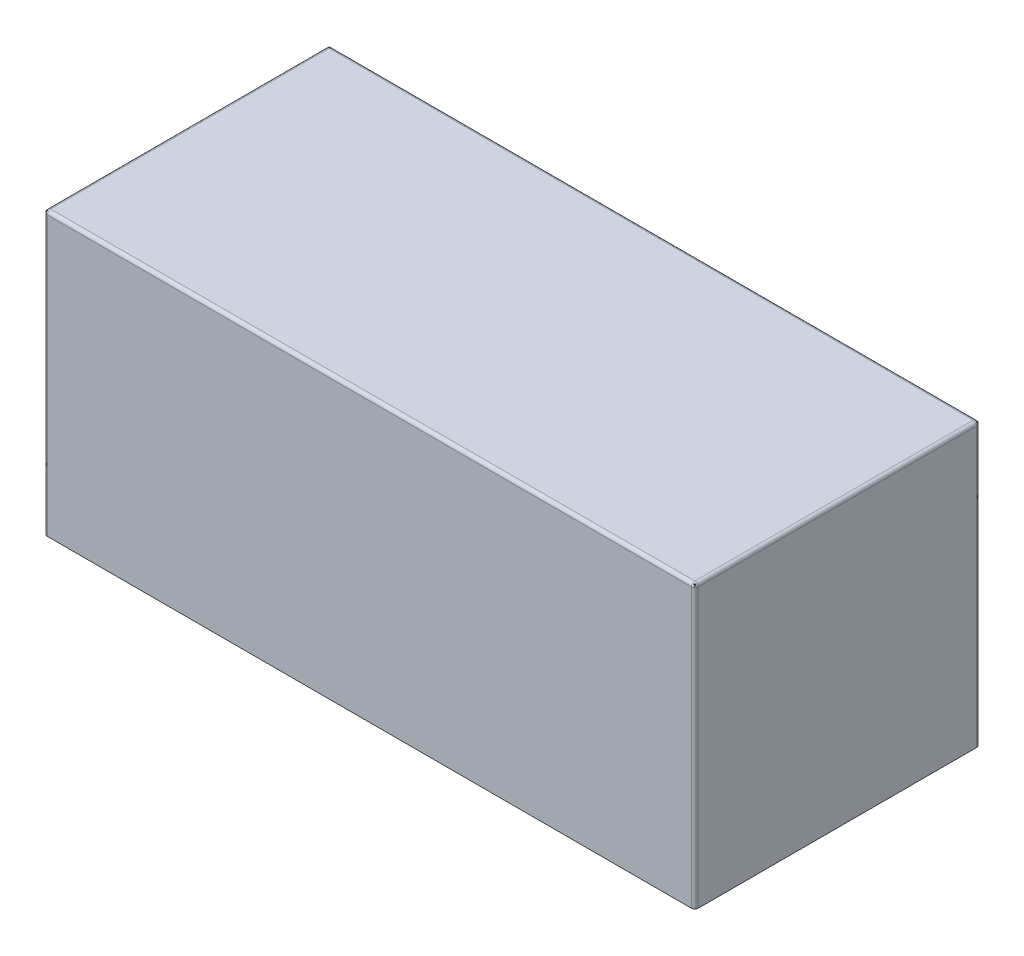
SolidWorks part; units mm, degrees
ref_plane "Front Plane" through (0, 0, 0) normal (0, 0, 1) x (1, 0, 0)
ref_plane "Top Plane" through (0, 0, 0) normal (0, 1, 0) x (1, 0, 0)
ref_plane "Right Plane" through (0, 0, 0) normal (1, 0, 0) x (0, 0, -1)
sketch "Sketch2" plane through (0, 0, 0) normal (0, 1, 0) x (1, 0, 0)
  line L1 (-485, 212.5) -> (485, 212.5)
  line L2 (-485, 212.5) -> (-485, -212.5)
  line L3 (-485, -212.5) -> (485, -212.5)
  line L4 (485, 212.5) -> (485, -212.5)
  line L5 (-485, 212.5) -> (485, -212.5) construction
  line L6 (-485, -212.5) -> (485, 212.5) construction
  line L7 (-483.4125, 210.9125) -> (483.4125, 210.9125)
  line L8 (-483.4125, 210.9125) -> (-483.4125, -210.9125)
  line L9 (-483.4125, -210.9125) -> (483.4125, -210.9125)
  line L10 (483.4125, 210.9125) -> (483.4125, -210.9125)
  line L11 (-483.4125, 210.9125) -> (483.4125, -210.9125) construction
  line L12 (-483.4125, -210.9125) -> (483.4125, 210.9125) construction
  point P0 (0, 0)
  point P6 (0, 0)
  dimension "D1" = 970
  dimension "D2" = 425
  dimension "D3" = 966.825
  dimension "D4" = 421.825
extrude "Boss-Extrude1" add sketch "Sketch2" along normal blind 420
sketch "Sketch3" plane through (0, 0, 0) normal (0, 1, 0) x (1, 0, 0)
  line L1 (-485, 212.5) -> (485, 212.5)
  line L2 (-485, 212.5) -> (-485, -212.5)
  line L3 (-485, -212.5) -> (485, -212.5)
  line L4 (485, 212.5) -> (485, -212.5)
  line L5 (-485, 212.5) -> (485, -212.5) construction
  line L6 (-485, -212.5) -> (485, 212.5) construction
  point P0 (0, 0)
  dimension "D1" = 970
  dimension "D2" = 425
extrude "Boss-Extrude2" add sketch "Sketch3" against normal blind 1.5875 from offset 420
fillet "Fillet2" radius 5 8 edges at (0, 420, 212.5) (-485, 420, 0) (0, 420, -212.5) (485, 420, 0) (485, 210, 212.5) (-485, 210, 212.5) (-485, 210, -212.5) (485, 210, -212.5)
equation "\"sheetMetalThickness\"= 1in / 16"
equation "\"shellLength\" = 970mm"
equation "\"shellWidth\"= 425mm"
equation "\"shellHeight\" = 420mm"
equation "\"D1@Sketch2\"=\"shellLength\""
equation "\"D2@Sketch2\"=\"shellWidth\""
equation "\"D3@Sketch2\"=\"shellLength\"-\"sheetMetalThickness\"*2"
equation "\"D4@Sketch2\"=\"shellWidth\"-\"sheetMetalThickness\"*2"
equation "\"D1@Boss-Extrude1\"=\"shellHeight\""
equation "\"D1@Sketch3\"=\"shellLength\""
equation "\"D2@Sketch3\"=\"shellWidth\""
equation "\"D19@Boss-Extrude2\"=\"shellHeight\""
equation "\"D1@Boss-Extrude2\"=\"sheetMetalThickness\""
